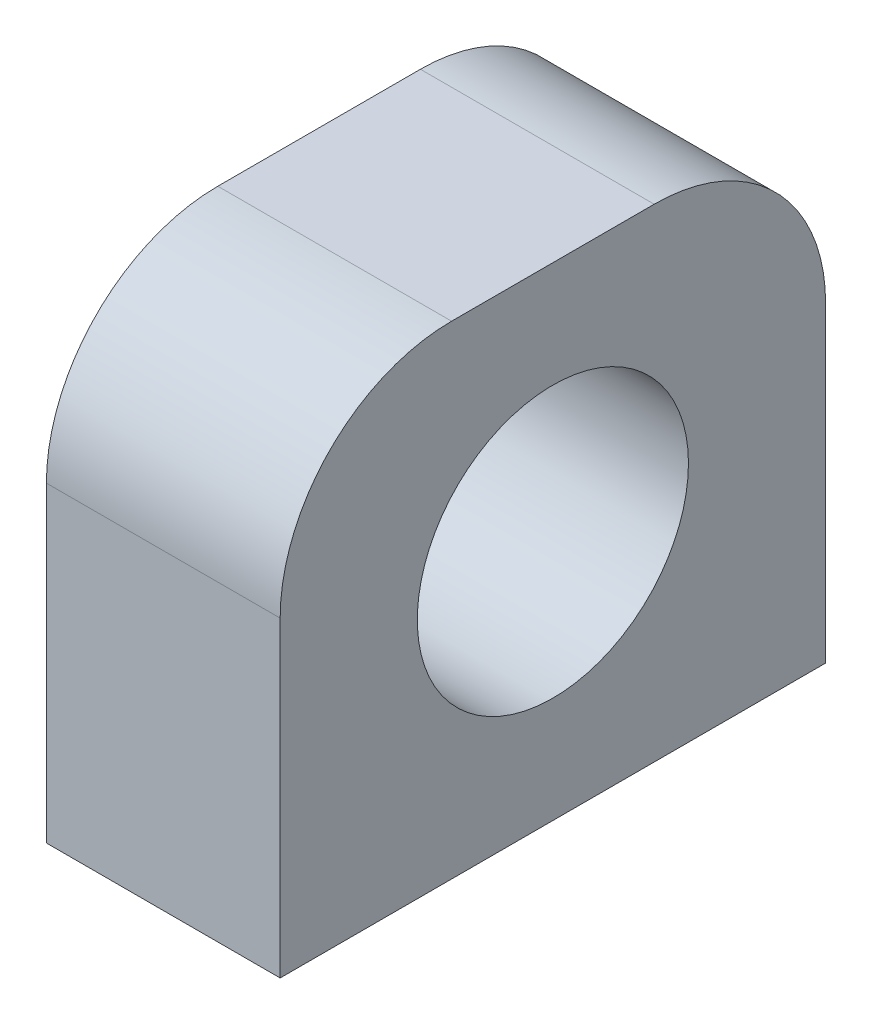
SolidWorks part; units mm, degrees
ref_plane "Front Plane" through (0, 0, 0) normal (0, 0, 1) x (1, 0, 0)
ref_plane "Top Plane" through (0, 0, 0) normal (0, 1, 0) x (1, 0, 0)
ref_plane "Right Plane" through (0, 0, 0) normal (1, 0, 0) x (0, 0, -1)
sketch "Sketch1" plane through (0, 0, 0) normal (1, 0, 0) x (0, 0, -1)
  line L1 (-22.225, -19.685) -> (22.225, -19.685)
  line L2 (-22.225, -19.685) -> (-22.225, 19.685)
  line L3 (-22.225, 19.685) -> (22.225, 19.685)
  line L4 (22.225, -19.685) -> (22.225, 19.685)
  line L5 (-22.225, -19.685) -> (22.225, 19.685) construction
  line L6 (-22.225, 19.685) -> (22.225, -19.685) construction
  point P0 (0, 0)
  dimension "D1" = 39.37
  dimension "D2" = 44.45
extrude "Boss-Extrude1" add sketch "Sketch1" along normal blind 19.05
sketch "Sketch2" plane through (19.05, 0, 0) normal (1, 0, 0) x (0, 0, -1)
  circle A0 centre (0, 0) radius 11.049
  dimension "D1" = 22.098
extrude "Cut-Extrude1" cut sketch "Sketch2" against normal blind 19.05
fillet "Fillet1" radius 13.97 2 edges at (9.525, 19.685, 22.225) (9.525, 19.685, -22.225)
